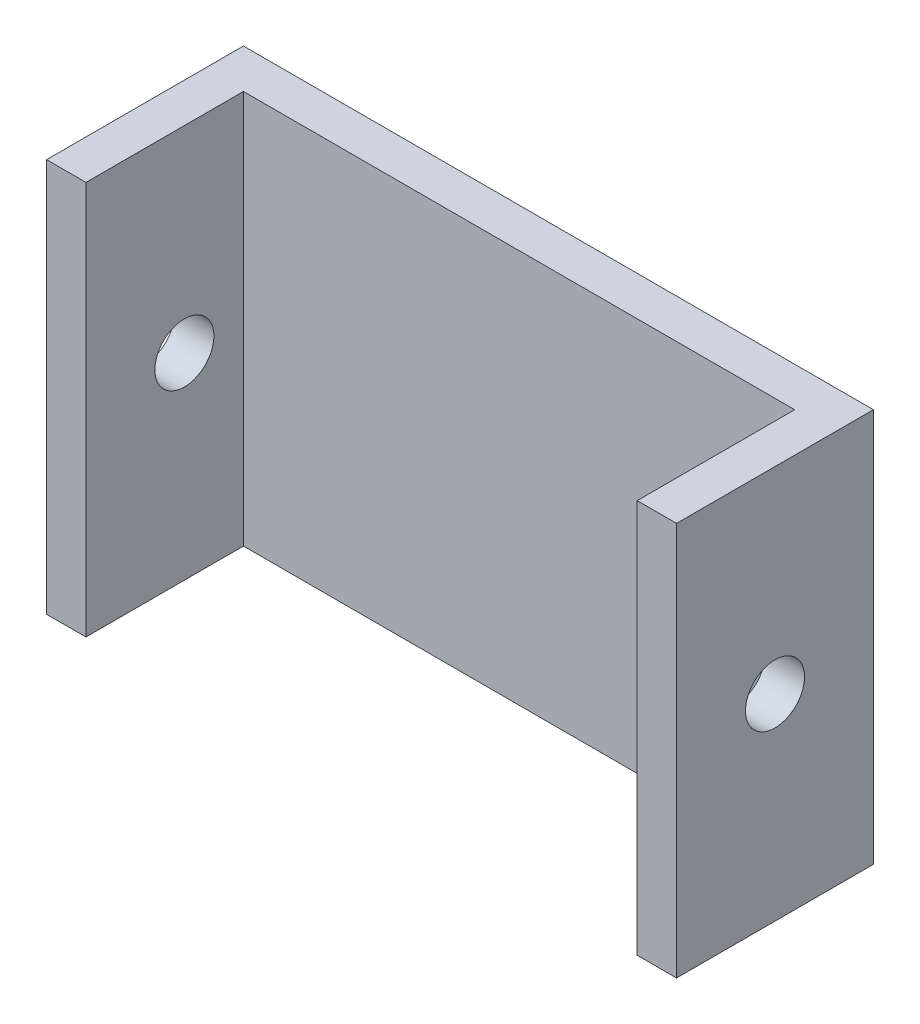
SolidWorks part; units mm, degrees
ref_plane "Plan de face" through (0, 0, 0) normal (0, 0, 1) x (1, 0, 0)
ref_plane "Plan de dessus" through (0, 0, 0) normal (0, 1, 0) x (1, 0, 0)
ref_plane "Plan de droite" through (0, 0, 0) normal (1, 0, 0) x (0, 0, -1)
sketch "Esquisse1" plane through (0, 0, 0) normal (0, 0, 1) x (1, 0, 0)
  line L1 (-14, 10) -> (14, 10)
  line L2 (-14, 10) -> (-14, -10)
  line L3 (-14, -10) -> (14, -10)
  line L4 (14, 10) -> (14, -10)
  line L5 (-14, 10) -> (14, -10) construction
  line L6 (-14, -10) -> (14, 10) construction
  point P0 (0, 0)
  dimension "D1" = 28
  dimension "D2" = 20
extrude "Boss.-Extru.1" add sketch "Esquisse1" along normal blind 2
sketch "Esquisse2" plane through (0, 0, 0) normal (0, 0, 1) x (1, 0, 0)
  line L0 (-14, -10) -> (-16, -10)
  line L1 (-16, -10) -> (-16, 10)
  line L2 (-16, 10) -> (-14, 10)
  line L3 (-14, 10) -> (-14, -10)
  line L8 (0, -13.5768) -> (0, 16.1891) construction
  line L9 (16, 10) -> (14, 10)
  line L10 (16, -10) -> (16, 10)
  line L11 (14, -10) -> (16, -10)
  line L12 (14, 10) -> (14, -10)
  dimension "D1" = 2
extrude "Boss.-Extru.2" add sketch "Esquisse2" along normal blind 10
sketch "Esquisse3" plane through (0, 0, 0) normal (1, 0, 0) x (0, 0, -1)
  circle A0 centre (-5, 0) radius 1.5
  point P2 (0, 0)
  dimension "D2" = 3
  dimension "D1" = 5
extrude "Enlèv. mat.-Extru.1" cut sketch "Esquisse3" against normal through all both and the other way through all
sketch "Esquisse4" plane through (0, 0, 0) normal (0, 0, -1) x (-1, 0, 0)
  line L0 (-16, -10) -> (-16, 10) construction
  line L1 (-16, 10) -> (16, 10) construction
  text T0 "<b>MQ-2 SENSOR</b>" font "Century Gothic" height in points 12
  dimension "D1" = 1
  dimension "D2" = 11
extrude "Enlèv. mat.-Extru.2" cut sketch "Esquisse4" against normal blind 1
